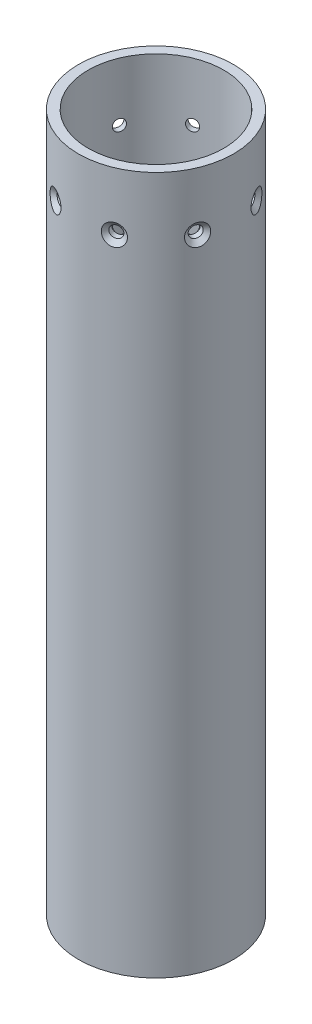
SolidWorks part; units mm, degrees
material "6061-T6 (SS)"
ref_plane "Front Plane" through (0, 0, 0) normal (0, 0, 1) x (1, 0, 0)
ref_plane "Top Plane" through (0, 0, 0) normal (0, 1, 0) x (1, 0, 0)
ref_plane "Right Plane" through (0, 0, 0) normal (1, 0, 0) x (0, 0, -1)
sketch "Sketch1" plane through (0, 0, 0) normal (0, 1, 0) x (1, 0, 0)
  circle A0 centre (0, 0) radius 25.4
  circle A1 centre (0, 0) radius 22.225
  dimension "D1" = 50.8
  dimension "D2" = 3.175
extrude "body" add sketch "Sketch1" along normal blind 228.6
hole_wizard "CSK for #6 Flat Head Machine Screw (100) Bottom, front aligned" [suppressed] positions "3DSketch1" profile "Sketch2" countersink size "#6" standard "ANSI Inch"
sketch3d "3DSketch1"
  point P0 (25.4, 19.05, 0)
  dimension "D1" = 19.05
sketch "Sketch2" plane through (25.4, 19.05, 0) normal (0, 1, 0) x (0, 0, -1)
  line L0 (0, 0) -> (0, 4.3158)
  line L1 (0, 4.3158) -> (1.8986, 3.175)
  line L2 (1.8986, 3.175) -> (1.8986, 1.38)
  line L3 (1.8986, 1.38) -> (3.5433, 0)
  line L5 (3.5433, 0) -> (0, 0)
  line L6 (-1.8986, 1.38) -> (-3.5433, 0) construction
  line L10 (0, 4.3158) -> (-1.8986, 3.175) construction
  line L11 (0, -6.35) -> (0, 107.95) construction
  dimension "Hole Dia." = 3.7973
  dimension "Hole Depth" = 3.175
  dimension "Near C'Sink Dia." = 7.0866
  dimension "Near C'Sink Angle" = 100
  dimension "Drill Angle" = 118
pattern_circular "bottom-bolt-pattern" [suppressed] count 8 over 360
ref_plane "offset reference" through (9.7202, 0, -23.4665) normal (0.3827, 0, -0.9239) x (0, -1, 0)
hole_wizard "CSK for #6 Flat Head Machine Screw (100) Top, offset" positions "3DSketch3" profile "Sketch4" countersink size "#6" standard "ANSI Inch"
sketch3d "3DSketch3"
  point P0 (9.7202, 209.55, -23.4665)
  dimension "D1" = 19.05
sketch "Sketch4" plane through (9.7202, 209.55, -23.4665) normal (0, 1, 0) x (-0.9239, 0, -0.3827)
  line L0 (0, 0) -> (0, 4.3158)
  line L1 (0, 4.3158) -> (1.8986, 3.175)
  line L2 (1.8986, 3.175) -> (1.8986, 1.38)
  line L3 (1.8986, 1.38) -> (3.5433, 0)
  line L5 (3.5433, 0) -> (0, 0)
  line L6 (-1.8986, 1.38) -> (-3.5433, 0) construction
  line L10 (0, 4.3158) -> (-1.8986, 3.175) construction
  line L11 (0, -6.35) -> (0, 107.95) construction
  dimension "Hole Dia." = 3.7973
  dimension "Hole Depth" = 3.175
  dimension "Near C'Sink Dia." = 7.0866
  dimension "Near C'Sink Angle" = 100
  dimension "Drill Angle" = 118
pattern_circular "top-bolt-pattern" count 8 over 360 about axis through (0, 228.6, 0) along (0, -1, 0) of "CSK for #6 Flat Head Machine Screw (100) Top, offset"
ref_plane "Vent Reference" [suppressed] through (0, 0, 25.4) normal (0, 0, 1) x (1, 0, 0)
hole_wizard "1/8 (0.125) Diameter Hole1" [suppressed] positions "Sketch5" profile "Sketch6" hole size "1/8" standard "ANSI Inch"
sketch "Sketch5" plane through (0, 0, 25.4) normal (0, 0, 1) x (1, 0, 0)
  line L0 (0, 0) -> (-14.2035, 0) construction
  line L1 (-25.4, 0) -> (25.4, 0) construction
  point P0 (-10.16, 2.54)
  dimension "D1" = 2.54
  dimension "D2" = 10.16
sketch "Sketch6" plane through (-10.16, 2.54, 25.4) normal (1, 0, 0) x (0, -1, 0)
  line L0 (0, 0) -> (0, 13.6539)
  line L1 (0, 13.6539) -> (1.5875, 12.7)
  line L2 (1.5875, 12.7) -> (1.5875, 0)
  line L5 (1.5875, 0) -> (0, 0)
  line L10 (0, 13.6539) -> (-1.5875, 12.7) construction
  line L11 (0, -6.35) -> (0, 107.95) construction
  dimension "Hole Dia." = 3.175
  dimension "Hole Depth" = 12.7
  dimension "Drill Angle" = 118
equation "\"TubeThick\"=0.125"
equation "\"D2@Sketch1\"=\"TubeThick\""
equation "\"Length\"=12"
equation "\"TubeLen\"=12"
